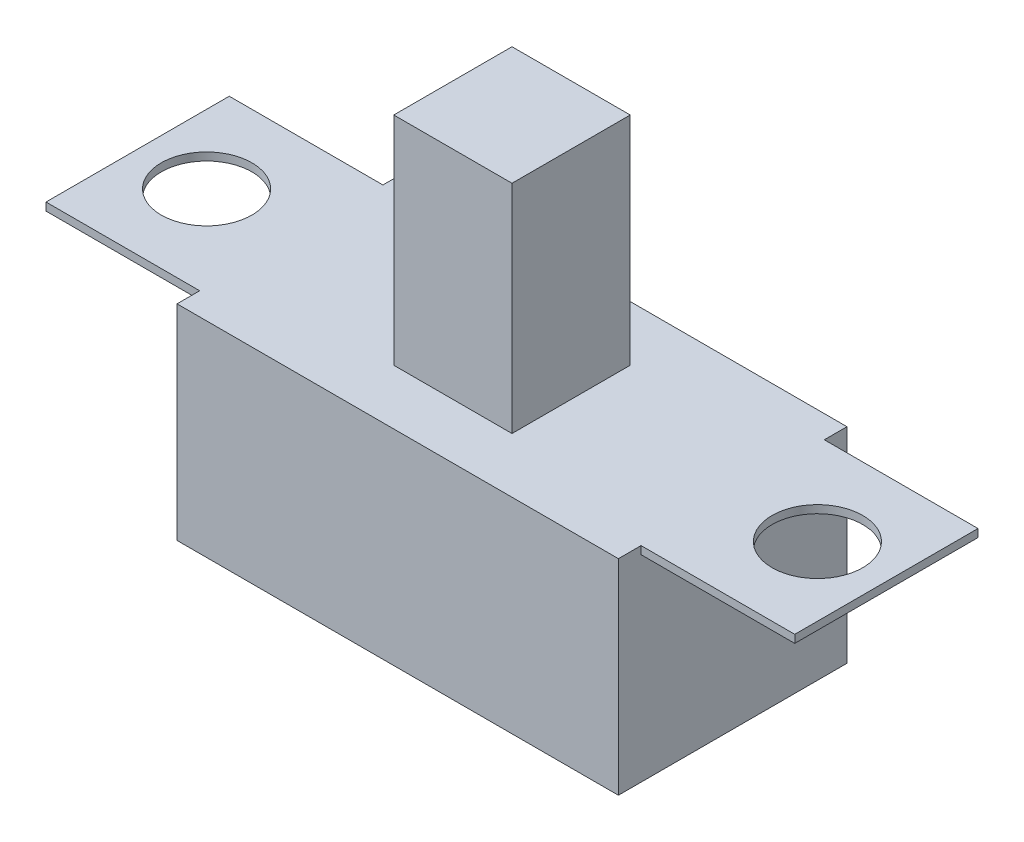
SolidWorks part; units mm, degrees
ref_plane "Front Plane" through (0, 0, 0) normal (0, 0, 1) x (1, 0, 0)
ref_plane "Top Plane" through (0, 0, 0) normal (0, 1, 0) x (1, 0, 0)
ref_plane "Right Plane" through (0, 0, 0) normal (1, 0, 0) x (0, 0, -1)
sketch "Sketch1" plane through (0, 0, 0) normal (0, 1, 0) x (1, 0, 0)
  line L0 (9.5, 2.325) -> (9.5, -2.325)
  line L1 (9.5, -2.325) -> (5.6, -2.325)
  line L2 (5.6, -2.325) -> (5.6, -2.9)
  line L3 (5.6, -2.9) -> (-5.6, -2.9)
  line L4 (-5.6, -2.9) -> (-5.6, -2.325)
  line L5 (-5.6, -2.325) -> (-9.5, -2.325)
  line L6 (-9.5, -2.325) -> (-9.5, 2.325)
  line L7 (-9.5, 2.325) -> (-5.6, 2.325)
  line L8 (-5.6, 2.325) -> (-5.6, 2.9)
  line L9 (-5.6, 2.9) -> (5.6, 2.9)
  line L10 (5.6, 2.9) -> (5.6, 2.325)
  line L11 (5.6, 2.325) -> (9.5, 2.325)
  circle A0 centre (-7.75, 0) radius 1.15
  circle A1 centre (7.75, 0) radius 1.15
  point P14 (0, -2.9)
  point P16 (-9.5, 0)
  point P19 (0, 0)
  dimension "D9" = 2.3
  dimension "D10" = 2.3
  dimension "D1" = 19
  dimension "D2" = 4.65
  dimension "D3" = 11.2
  dimension "D4" = 11.2
  dimension "D5" = 4.65
  dimension "D6" = 5.8
  dimension "D7" = 2.9
  dimension "D8" = 9.5
  dimension "D11" = 15.5
  dimension "D12" = 7.75
extrude "Boss-Extrude1" add sketch "Sketch1" along normal blind 0.2
sketch "Sketch2" plane through (0, 0, 0) normal (0, -1, 0) x (1, 0, 0)
  line L1 (-5.6, 2.9) -> (5.6, 2.9)
  line L2 (-5.6, 2.9) -> (-5.6, -2.9)
  line L3 (-5.6, -2.9) -> (5.6, -2.9)
  line L4 (5.6, 2.9) -> (5.6, -2.9)
extrude "Boss-Extrude2" add sketch "Sketch2" along normal blind 5
sketch "Sketch3" plane through (0, 0.2, 0) normal (0, 1, 0) x (1, 0, 0)
  line L1 (-1.5, 1.5) -> (1.5, 1.5)
  line L2 (-1.5, 1.5) -> (-1.5, -1.5)
  line L3 (-1.5, -1.5) -> (1.5, -1.5)
  line L4 (1.5, 1.5) -> (1.5, -1.5)
  line L5 (-1.5, 1.5) -> (1.5, -1.5) construction
  line L6 (-1.5, -1.5) -> (1.5, 1.5) construction
  point P0 (0, 0)
  dimension "D1" = 3
  dimension "D2" = 3
extrude "Boss-Extrude3" add sketch "Sketch3" along normal blind 5.5
